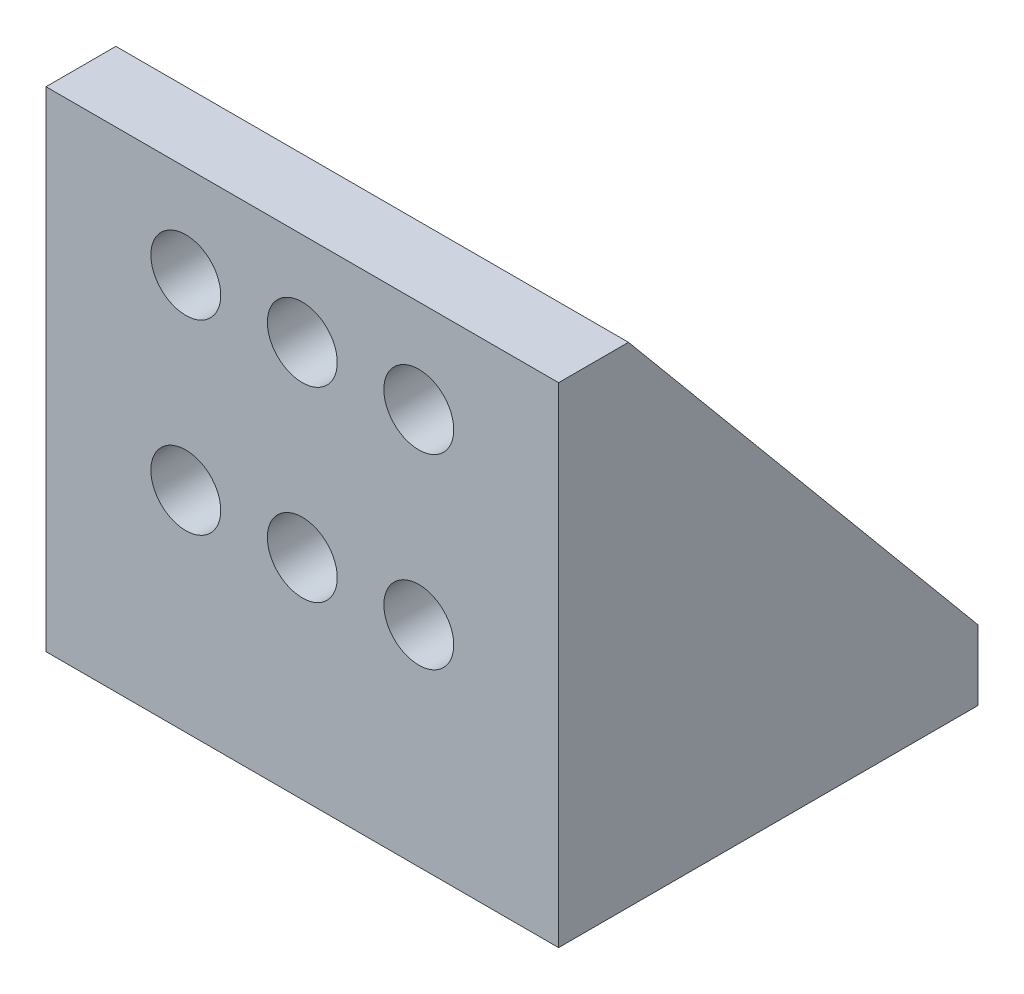
SolidWorks part; units mm, degrees
material "POM 乙缩醛共聚物"
ref_plane "前视基准面" through (0, 0, 0) normal (0, 0, 1) x (1, 0, 0)
ref_plane "上视基准面" through (0, 0, 0) normal (0, 1, 0) x (1, 0, 0)
ref_plane "右视基准面" through (0, 0, 0) normal (1, 0, 0) x (0, 0, -1)
sketch "草图1" plane through (0, 0, 0) normal (1, 0, 0) x (0, 0, -1)
  line L0 (0, 0) -> (0, 21)
  line L5 (0, 21) -> (3, 21)
  line L6 (3, 21) -> (3, 3)
  line L7 (3, 3) -> (18, 3)
  line L8 (18, 3) -> (18, 0)
  line L9 (18, 0) -> (0, 0)
  dimension "D1" = 18
  dimension "D2" = 3
  dimension "D3" = 21
extrude "凸台-拉伸1" add sketch "草图1" along normal blind 22
sketch "草图2" plane through (0, 3, 0) normal (0, 1, 0) x (1, 0, 0)
  line L0 (11, 3) -> (11, 5.8) construction
  line L1 (22, 3) -> (0, 3) construction
  circle A0 centre (11, 5.8) radius 1.5
  circle A1 centre (11, 13.8) radius 1.5
  circle A2 centre (16, 5.8) radius 1.5
  circle A3 centre (16, 13.8) radius 1.5
  circle A4 centre (6, 13.8) radius 1.5
  circle A5 centre (6, 5.8) radius 1.5
  dimension "D2" = 3
  dimension "D1" = 2.8
  dimension "D3" = 8
  dimension "D4" = 5
extrude "切除-拉伸1" cut sketch "草图2" against normal blind 13
sketch "草图3" plane through (22, 0, 0) normal (1, 0, 0) x (0, 0, -1)
  line L0 (3, 21) -> (18, 3)
  line L1 (18, 3) -> (3, 3)
  line L2 (3, 3) -> (3, 21)
extrude "凸台-拉伸2" add sketch "草图3" against normal blind 3
sketch "草图4" plane through (0, 0, 0) normal (-1, 0, 0) x (0, 0, 1)
  line L0 (-18, 3) -> (-3, 3)
  line L1 (-3, 3) -> (-3, 21)
  line L2 (-3, 21) -> (-18, 3)
extrude "凸台-拉伸3" add sketch "草图4" against normal blind 3
sketch "草图5" plane through (0, 0, 0) normal (0, 0, 1) x (1, 0, 0)
  line L0 (11, 21) -> (11, 17) construction
  line L1 (22, 21) -> (0, 21) construction
  line L2 (12.7, 24.1602) -> (12.7, 18.2296) construction
  line L3 (0, 21) -> (0, 0) construction
  line L4 (-0.5, 24.1602) -> (-0.5, 15.1454) construction
  circle A0 centre (11, 17) radius 1.5
  circle A1 centre (11, 9) radius 1.5
  circle A2 centre (6, 17) radius 1.5
  circle A3 centre (6, 9) radius 1.5
  circle A4 centre (16, 9) radius 1.5
  circle A5 centre (16, 17) radius 1.5
  dimension "D1" = 3
  dimension "D2" = 4
  dimension "D3" = 8
  dimension "D4" = 5
  dimension "D5" = 12.7
  dimension "D6" = 6.7
  dimension "D7" = 6.5
extrude "切除-拉伸2" cut sketch "草图5" against normal blind 3
